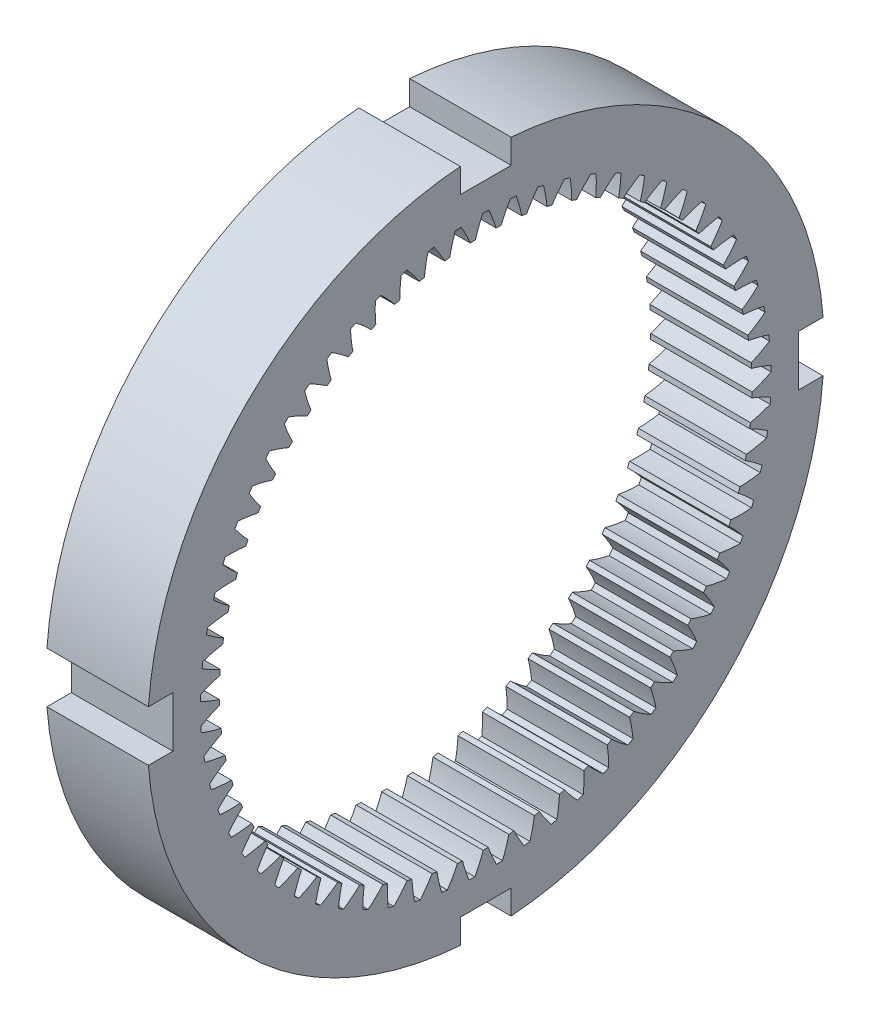
SolidWorks part; units mm, degrees
ref_plane "Plane1" through (0, 0, 0) normal (0, 0, 1) x (1, 0, 0)
ref_plane "Plane2" through (0, 0, 0) normal (0, 1, 0) x (1, 0, 0)
ref_plane "Plane3" through (0, 0, 0) normal (1, 0, 0) x (0, 0, -1)
sketch "HoldingSke" plane through (0, 0, 0) normal (0, 1, 0) x (1, 0, 0)
  line L0 (0, 0) -> (0.4226, -0.9063)
  line L1 (-15, 0) -> (100, 0) construction
  line L2 (0, 0) -> (-2.1039, 2.3779)
  line L3 (0, 0) -> (-11.863, 4.5341)
  line L4 (0, 0) -> (3.6497, 7.8269)
  line L5 (0, 0) -> (-23.7986, -8.8762)
  line L6 (0, 0) -> (-10.5278, -7.1032)
  line L7 (-2.1039, 2.3779) -> (3.3635, 27.1825)
  line L8 (-76.2, 3.3779) -> (-54.61, 3.3779)
  line L9 (-71.009, 38.7566) -> (-53.1078, 45.2721)
  line L10 (-76.2, 71.12) -> (104.1128, 71.12)
  line L11 (0, 0) -> (-12, 0)
  line L12 (-76.2, 101.6) -> (-76.162, 101.6)
  line L13 (24.9733, 27.94) -> (52.9518, 28.4284)
  line L14 (24.9733, 27.94) -> (24.9743, 27.94)
  line L15 (24.9733, 27.94) -> (100.4006, 29.5858)
  circle A0 centre (0, 0) radius 35
  circle A1 centre (0, 0) radius 12.7
  circle A2 centre (0, 0) radius 12.7
  dimension "MHD" = 25.4
  dimension "Hub_dia" = 25.4
  dimension "Diameter" = 70
  dimension "Num_teeth" = 65
  dimension "Pitch" = 1
  dimension "Overall_len" = 25.4
  dimension "Show_teeth" = 65
  dimension "Thickness" = 12.7
  dimension "OAL" = 25.4001
  dimension "T_dim" = 21.59
  dimension "Ap" = 20
  dimension "H" = 19.05
  dimension "Pitch_radius" = 180.3128
  dimension "Width" = 12
  dimension "Backlash" = 0.038
  dimension "Addendum_fac" = 1
  dimension "Dedendum_fac" = 1.25
  dimension "Clearance_fac" = 0.25
  dimension "Dedendum_add" = 0.001
  dimension "Module" = 1
sketch "BasProSke" plane through (0, 0, 0) normal (0, 1, 0) x (1, 0, 0)
  line L0 (-10, 0) -> (60, 0) construction
  line L1 (0, 31.5) -> (0, 35)
  line L2 (0, 31.5) -> (12, 31.5)
  line L3 (12, 31.5) -> (12, 35)
  line L4 (12, 35) -> (0, 35)
  dimension "Diameter" = 70
  dimension "Thickness" = 12
  dimension "Inside_diameter" = 63
revolve "Base-Revolve" add sketch "BasProSke" angle 360 about L0
sketch "TooCutSke" plane through (0, 0, 0) normal (1, 0, 0) x (0, 0, -1)
  line L3 (0.8803, 32.4881) -> (0.8803, 53.6633) construction
  line L4 (0, 0) -> (0, 59.563) construction
  line L5 (0, 0) -> (-3.3011, 68.2477) construction
  line L6 (-14.3506, 26.824) -> (36.4707, 29.2822) construction
  circle A0 centre (0, 0) radius 32.5 construction
  circle A1 centre (0, 0) radius 33.751 construction
  circle A2 centre (0, 0) radius 27.486 construction
  circle A3 centre (0, 0) radius 31.4746 construction
  arc A4 (1.2268, 31.4507) -> (0.3499, 33.7492) centre (-14.3506, 26.824) ccw
  arc A5 (1.2268, 31.4507) -> (-1.2268, 31.4507) centre (0, 0) ccw
  arc A6 (0.3499, 33.7492) -> (-0.3499, 33.7492) centre (0, 0) ccw
  arc A7 (-0.3499, 33.7492) -> (-1.2268, 31.4507) centre (14.3506, 26.824) ccw
  dimension "Pitch_dia" = 65
  dimension "Base_dia" = 54.972
  dimension "Root_dia" = 67.502
  dimension "Overcut_dia" = 62.9492
  dimension "Flank_rad" = 16.25
  dimension "Half_ang" = 2.769
  dimension "Half_CT" = 0.8803
extrude "ToothCut" cut sketch "TooCutSke" along normal through all
fillet "Breaks" [suppressed] radius 0.1
fillet "RootFillets" [suppressed] radius 0.251
pattern_circular "TeethCuts" count 65 every 5.538 about axis through (-10, 0, 0) along (1, 0, 0) of "RootFillets", "Breaks", "ToothCut"
sketch "Sketch1" plane through (12, 0, 0) normal (1, 0, 0) x (0, 0, -1)
  line L0 (0, 0) -> (0, 40) construction
  line L1 (39.8873, 3) -> (37, 3)
  line L3 (-3, 39.8873) -> (-3, 37)
  line L4 (-3, 37) -> (3, 37)
  line L5 (3, 39.8873) -> (3, 37)
  line L6 (37, 3) -> (37, -3)
  line L7 (39.8873, -3) -> (37, -3)
  line L8 (3, -39.8873) -> (3, -37)
  line L9 (3, -37) -> (-3, -37)
  line L10 (-3, -39.8873) -> (-3, -37)
  line L11 (-39.8873, -3) -> (-37, -3)
  line L12 (-37, -3) -> (-37, 3)
  line L13 (-39.8873, 3) -> (-37, 3)
  circle A0 centre (0, 0) radius 35 construction
  circle A1 centre (0, 0) radius 35
  arc A2 (-3, 39.8873) -> (-39.8873, 3) centre (0, 0) ccw
  arc A3 (-39.8873, -3) -> (-3, -39.8873) centre (0, 0) ccw
  arc A4 (3, -39.8873) -> (39.8873, -3) centre (0, 0) ccw
  arc A5 (39.8873, 3) -> (3, 39.8873) centre (0, 0) ccw
  point P9 (0, 37)
  point P25 (0, 0)
  dimension "D1" = 80
  dimension "D2" = 6
  dimension "D3" = 3
  dimension "D4" = 4
extrude "Boss-Extrude1" add sketch "Sketch1" against normal up to surface (12 mm away) up to face at (0, 0, 35)
sketch "Sketch2" plane through (12, 0, 0) normal (1, 0, 0) x (0, 0, -1)
  circle A0 centre (0, 0) radius 32.5 construction
  dimension "D1" = 65
equation "' \"Module@HoldingSke\" = 6.35"
equation "' \"Num_teeth@HoldingSke\" = 24"
equation "' \"Ap@HoldingSke\" =  14.5"
equation "' \"Ap@HoldingSke\" = 14.5"
equation "' \"Width@HoldingSke\" = 12"
equation "' \"Diameter@HoldingSke\" = 8 * 25.4"
equation "' \"Show_teeth@HoldingSke\" = 100"
equation "' \"Backlash@HoldingSke\" = 0.009 * 25.4"
equation "' \"Addendum_fac@HoldingSke\" = 1.0"
equation "' \"Dedendum_fac@HoldingSke\" = 1.25"
equation "' \"Dedendum_add@HoldingSke\" = 0.00005 * 25.4"
equation "' \"Clearance_fac@HoldingSke\" = 0.25"
equation "\"Pitch@HoldingSke\" = 1 / \"Module@HoldingSke\" "
equation "\"Overcut_dia@TooCutSke\" = (\"Num_teeth@HoldingSke\" - 2 * \"Addendum_fac@HoldingSke\") / \"Pitch@HoldingSke\" - 0.002 * 25.4"
equation "\"Pitch_dia@TooCutSke\" = \"Num_teeth@HoldingSke\" / \"Pitch@HoldingSke\""
equation "\"Base_dia@TooCutSke\" = \"Num_teeth@HoldingSke\" / \"Pitch@HoldingSke\" * cos((\"Ap@HoldingSke\"  * 3.14159265 / 180)) * 0.90"
equation "\"Root_dia@TooCutSke\" = \"Num_teeth@HoldingSke\"  / \"Pitch@HoldingSke\" + 2 *  \"Dedendum_fac@HoldingSke\"/ \"Pitch@HoldingSke\" + \"Dedendum_add@HoldingSke\" * 2"
equation "\"Half_ang@TooCutSke\" = 180 / \"Num_teeth@HoldingSke\""
equation "\"Half_CT@TooCutSke\" = \"Num_teeth@HoldingSke\" / \"Pitch@HoldingSke\" * sin((3.14159265 / 2 / \"Num_teeth@HoldingSke\")) / 2 + 10 * \"Backlash@HoldingSke\" / 4"
equation "\"Flank_rad@TooCutSke\" = \"Num_teeth@HoldingSke\" / \"Pitch@HoldingSke\" / 4"
equation "\"Radius@RootFillets\"= \"Clearance_fac@HoldingSke\" / \"Pitch@HoldingSke\" + \"Dedendum_add@HoldingSke\""
equation "\"Break_rad@Breaks\" = 0.02 / \"Pitch@HoldingSke\" * 5"
equation "\"Num_teeth@TeethCuts\" = int( \"Show_teeth@HoldingSke\" ) + 1"
equation "\"Num_teeth@TeethCuts\" = ((sgn( \"Num_teeth@TeethCuts\" - \"Num_teeth@HoldingSke\" )-1)*( \"Num_teeth@TeethCuts\" - \"Num_teeth@HoldingSke\" ))/-2+ \"Num_teeth@HoldingSke\""
equation "\"Num_teeth@TeethCuts\" = ((sgn( \"Num_teeth@TeethCuts\" - 2.0)+1)*( \"Num_teeth@TeethCuts\" - 2.0))/2 +2.0"
equation "\"Angle@TeethCuts\" = 360.0 / \"Num_teeth@HoldingSke\""
equation "\"Diameter@BasProSke\" = \"Num_teeth@HoldingSke\"  / \"Pitch@HoldingSke\" + 2 *  \"Dedendum_fac@HoldingSke\"/ \"Pitch@HoldingSke\" + \"Dedendum_add@HoldingSke\" * 2 + 0.002 * 25.4"
equation "\"Diameter@BasProSke\" = ((sgn( \"Diameter@BasProSke\"  - \"Diameter@HoldingSke\" )+1)*( \"Diameter@BasProSke\"  - \"Diameter@HoldingSke\" ))/2 + \"Diameter@HoldingSke\""
equation "\"Inside_diameter@BasProSke\" =  (\"Num_teeth@HoldingSke\" - 2 * \"Addendum_fac@HoldingSke\") / \"Pitch@HoldingSke\" "
equation "\"Thickness@BasProSke\"  = \"Width@HoldingSke\""
